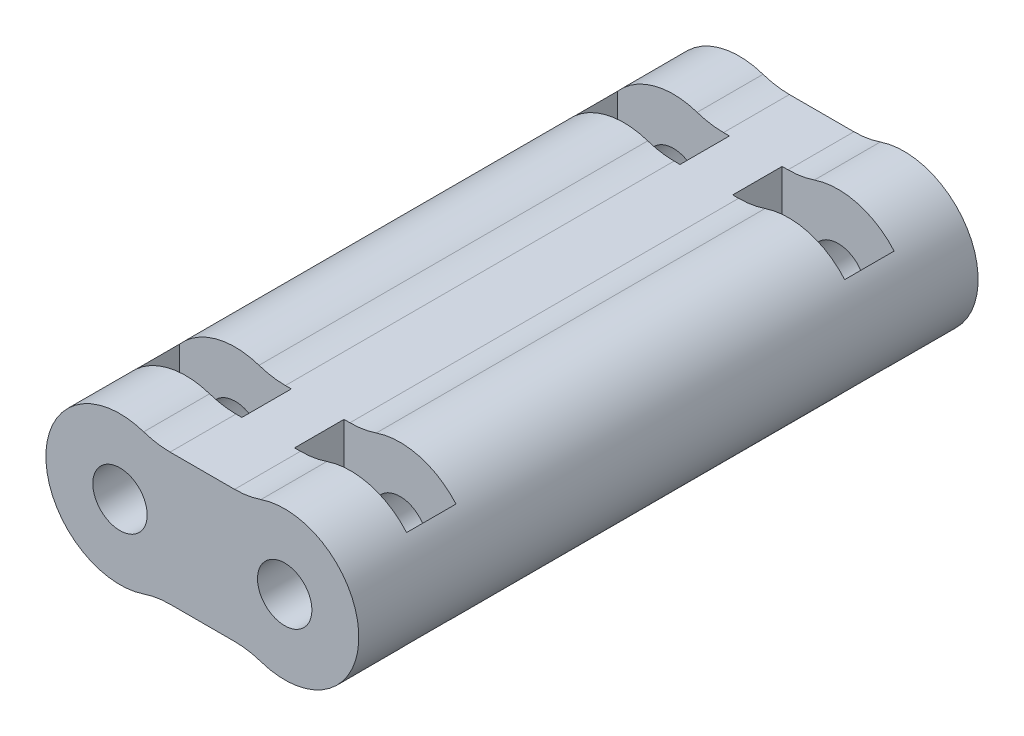
SolidWorks part; units mm, degrees
ref_plane "Plano frontal" through (0, 0, 0) normal (0, 0, 1) x (1, 0, 0)
ref_plane "Plano superior" through (0, 0, 0) normal (0, 1, 0) x (1, 0, 0)
ref_plane "Plano direito" through (0, 0, 0) normal (1, 0, 0) x (0, 0, -1)
sketch "Esboço1" plane through (0, 0, 0) normal (0, 0, 1) x (1, 0, 0)
  line L0 (0, 0) -> (0, 3.1709) construction
  line L1 (-2.9384, 4) -> (2.9384, 4)
  line L2 (-2.9384, -4) -> (2.9384, -4)
  line L3 (-1.0405, 0) -> (1.3443, 0) construction
  circle A0 centre (-5, 0) radius 1.65
  circle A1 centre (5, 0) radius 1.65
  arc A2 (-2.9384, 4) -> (-2.9384, -4) centre (-5, 0) ccw
  arc A3 (2.9384, -4) -> (2.9384, 4) centre (5, 0) ccw
  dimension "D1" = 3.3
  dimension "D3" = 9
  dimension "D2" = 10
  dimension "D4" = 8
extrude "Ressalto-extrusão1" add sketch "Esboço1" along normal blind 37.6
fillet "Filete1" radius 5 4 edges at (-2.9384, -4, 18.8) (2.9384, -4, 18.8) (2.9384, 4, 18.8) (-2.9384, 4, 18.8)
sketch "Esboço2" plane through (0, 0, 0) normal (0, 1, 0) x (1, 0, 0)
  line L0 (-5, 0) -> (-5, -37.6) construction
  line L1 (-3.35, 0) -> (-6.65, 0) construction
  line L2 (-9.5, -37.6) -> (-3.5593, -37.6) construction
  line L3 (-3.5593, 0) -> (-9.5, 0) construction
  line L4 (-8.4, -4) -> (-1.6, -4)
  line L5 (-8.4, -4) -> (-8.4, -7)
  line L6 (-8.4, -7) -> (-1.6, -7)
  line L7 (-1.6, -4) -> (-1.6, -7)
  line L8 (-8.4, -4) -> (-1.6, -7) construction
  line L9 (-8.4, -7) -> (-1.6, -4) construction
  line L10 (0, 0) -> (0, -42.0111) construction
  line L12 (-9.5, -18.8) -> (9.5, -18.8) construction
  line L13 (-9.5, 0) -> (-9.5, -37.6) construction
  line L14 (9.5, -37.6) -> (9.5, 0) construction
  line L15 (8.4, -7) -> (1.6, -4) construction
  line L16 (8.4, -4) -> (1.6, -7) construction
  line L17 (1.6, -4) -> (1.6, -7)
  line L18 (8.4, -7) -> (1.6, -7)
  line L19 (8.4, -4) -> (8.4, -7)
  line L20 (8.4, -4) -> (1.6, -4)
  line L21 (8.4, -33.6) -> (1.6, -30.6) construction
  line L22 (8.4, -30.6) -> (1.6, -33.6) construction
  line L23 (-8.4, -30.6) -> (-1.6, -33.6) construction
  line L24 (-8.4, -33.6) -> (-1.6, -30.6) construction
  line L25 (8.4, -33.6) -> (1.6, -33.6)
  line L26 (8.4, -33.6) -> (8.4, -30.6)
  line L27 (8.4, -30.6) -> (1.6, -30.6)
  line L28 (1.6, -33.6) -> (1.6, -30.6)
  line L29 (-1.6, -33.6) -> (-1.6, -30.6)
  line L30 (-8.4, -30.6) -> (-1.6, -30.6)
  line L31 (-8.4, -33.6) -> (-8.4, -30.6)
  line L32 (-8.4, -33.6) -> (-1.6, -33.6)
  point P6 (-5, -5.5)
  point P16 (0, -42.0111)
  point P28 (5, -5.5)
  point P37 (5, -32.1)
  point P38 (-5, -32.1)
  dimension "D1" = 3
  dimension "D2" = 6.8
  dimension "D3" = 4
extrude "Corte-extrusão1" cut sketch "Esboço2" against normal through all both and the other way through all contours L7 L4 L5 L6 | L19 L20 L17 L18 | L28 L25 L26 L27 | L31 L32 L29 L30
